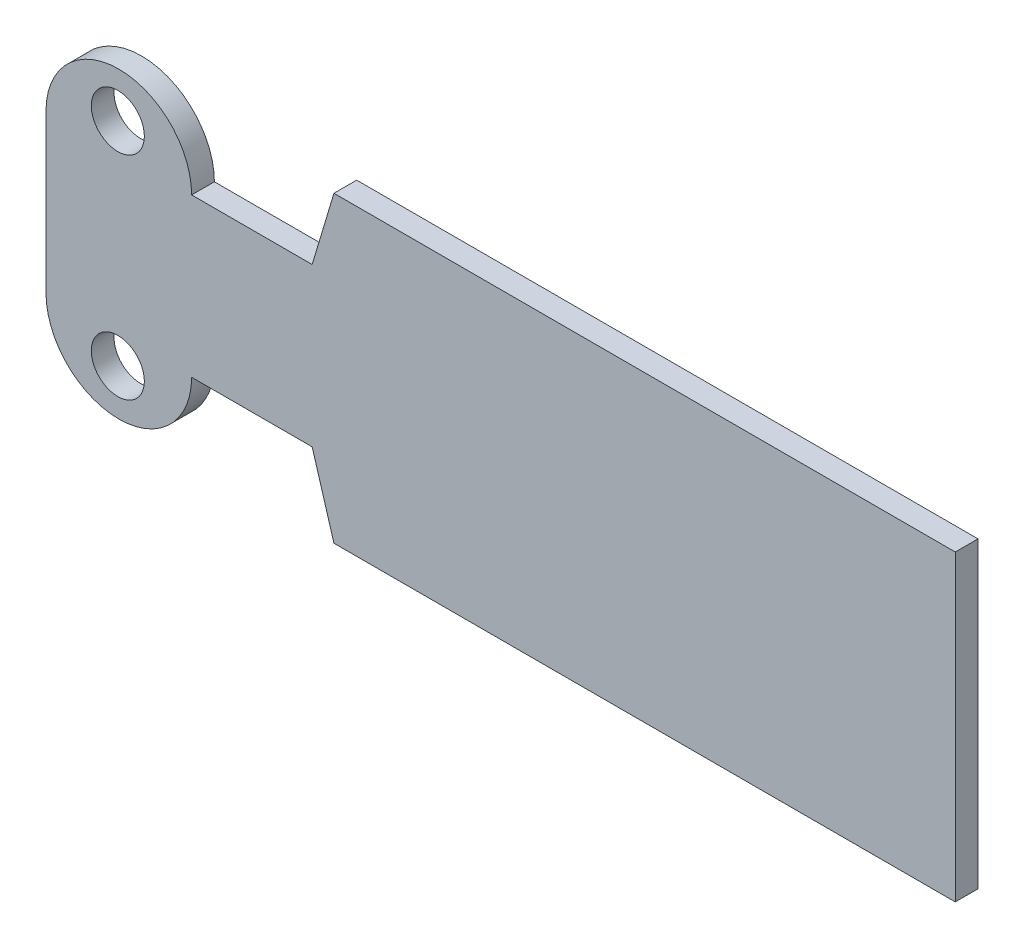
SolidWorks part; units mm, degrees
ref_plane "Front Plane" through (0, 0, 0) normal (0, 0, 1) x (1, 0, 0)
ref_plane "Top Plane" through (0, 0, 0) normal (0, 1, 0) x (1, 0, 0)
ref_plane "Right Plane" through (0, 0, 0) normal (1, 0, 0) x (0, 0, -1)
sketch "Sketch1" plane through (0, 0, 0) normal (0, 0, 1) x (1, 0, 0)
  line L0 (0, 0) -> (3, 10)
  line L1 (3, 10) -> (44, 10)
  line L2 (44, 10) -> (44, -10)
  line L3 (44, -10) -> (3, -10)
  line L4 (3, -10) -> (0, 0)
  line L5 (0, 0) -> (44, 0) construction
  line L6 (1.5633, -5.2109) -> (-6.3885, -5.2109)
  line L7 (-16, -5.2109) -> (-16, 5.2109)
  line L8 (1.5633, 5.2109) -> (-6.3885, 5.2109)
  arc A0 (-6.3885, -5.2109) -> (-16, -5.2109) centre (-11.1943, -5.1942) cw
  arc A1 (-6.3885, 5.2109) -> (-16, 5.2109) centre (-11.1943, 5.1942) ccw
  circle A3 centre (-11.2606, -7) radius 1.75
  circle A4 centre (-11.2606, 7) radius 1.75
  point P7 (44, 0)
  point P10 (-11.1943, -10)
  point P15 (0, 0)
  point P20 (-16, 0)
  point P21 (0, 0)
  point P22 (-44.3943, 6.4111)
  dimension "D6" = 4.8058
  dimension "D7" = 3
  dimension "D1" = 20
  dimension "D2" = 41
  dimension "D3" = 3
  dimension "D4" = 5
  dimension "D5" = 60
extrude "Boss-Extrude1" add sketch "Sketch1" along normal blind 1.5 contours L5 L4 L3 L2 | L0 L5 L2 L1 | L8 A1 L7 A0 L6 L4 L0 A3 A4
